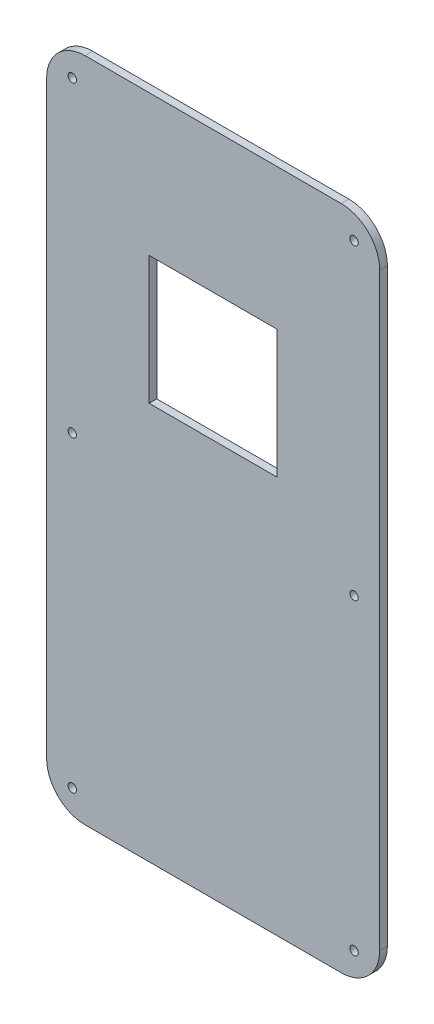
SolidWorks part; units mm, degrees
material "Thornel Mat VMA"
ref_plane "前视基准面" through (0, 0, 0) normal (0, 0, 1) x (1, 0, 0)
ref_plane "上视基准面" through (0, 0, 0) normal (0, 1, 0) x (1, 0, 0)
ref_plane "右视基准面" through (0, 0, 0) normal (1, 0, 0) x (0, 0, -1)
sketch "草图1" plane through (0, 0, 0) normal (0, 0, 1) x (1, 0, 0)
  line L1 (0, 0) -> (130, 0)
  line L2 (0, 0) -> (0, 260)
  line L3 (0, 260) -> (130, 260)
  line L4 (130, 0) -> (130, 260)
  dimension "D1" = 260
  dimension "D2" = 130
extrude "凸台-拉伸1" add sketch "草图1" along normal blind 3 contours L3 L4 L1 L2
sketch "草图2" plane through (0, 0, 3) normal (0, 0, 1) x (1, 0, 0)
  line L0 (0, 0) -> (174.0174, 0) construction
  line L1 (0, 15.9013) -> (0, 0) construction
  line L3 (0, 10) -> (130, 10) construction
  line L4 (130, 0) -> (130, 260) construction
  line L5 (65, 0) -> (65, 260) construction
  line L6 (0, 260) -> (130, 260) construction
  line L7 (0, 130) -> (130, 130) construction
  circle A0 centre (120, 10) radius 1.65
  circle A1 centre (10, 10) radius 1.65
  circle A2 centre (10, 250) radius 1.65
  circle A3 centre (120, 250) radius 1.65
  circle A4 centre (120, 130) radius 1.6
  circle A5 centre (10, 130) radius 1.605
  dimension "D5" = 3.3
  dimension "D6" = 3.3
  dimension "D8" = 3.2
  dimension "D9" = 3.21
  dimension "D1" = 10
  dimension "D2" = 65
  dimension "D3" = 10
  dimension "D4" = 10
  dimension "D7" = 130
  dimension "D10" = 10
  dimension "D11" = 10
extrude "切除-拉伸1" cut sketch "草图2" against normal blind 3
sketch "草图3" plane through (0, 0, 0) normal (0, 0, -1) x (-1, 0, 0)
  line L1 (-90, 155) -> (-40, 155)
  line L2 (-90, 155) -> (-90, 205)
  line L3 (-90, 205) -> (-40, 205)
  line L4 (-40, 155) -> (-40, 205)
  line L6 (-65, 260) -> (-65, 0) construction
  line L7 (0, 260) -> (-130, 260) construction
  line L8 (0, 0) -> (-130, 0) construction
  line L9 (-130, 180) -> (0, 180) construction
  line L10 (-130, 0) -> (-130, 260) construction
  line L11 (0, 0) -> (0, 260) construction
  dimension "D1" = 80
  dimension "D2" = 25
  dimension "D3" = 25
  dimension "D4" = 25
  dimension "D5" = 25
extrude "切除-拉伸2" cut sketch "草图3" against normal blind 10
fillet "圆角1" radius 15 4 edges at (0, 260, 1.5) (0, 0, 1.5) (130, 0, 1.5) (130, 260, 1.5)
